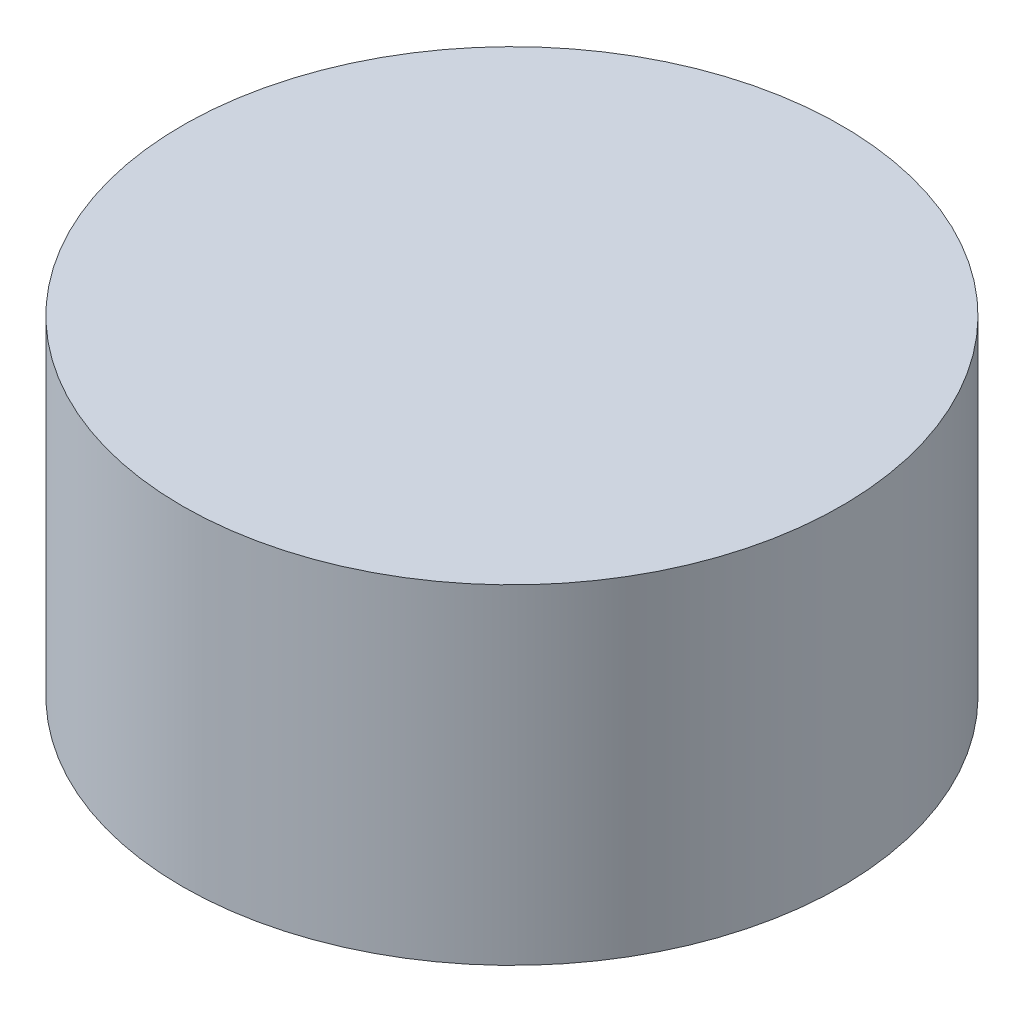
SolidWorks part; units mm, degrees
ref_plane "Front Plane" through (0, 0, 0) normal (0, 0, 1) x (1, 0, 0)
ref_plane "Top Plane" through (0, 0, 0) normal (0, 1, 0) x (1, 0, 0)
ref_plane "Right Plane" through (0, 0, 0) normal (1, 0, 0) x (0, 0, -1)
other "Configuration Table"
sketch "Sketch1" plane through (0, 0, 0) normal (0, 1, 0) x (1, 0, 0)
  circle A0 centre (0, 0) radius 12
extrude "VNT_govde_D24" add sketch "Sketch1" along normal blind 12 from offset 18 separate body
